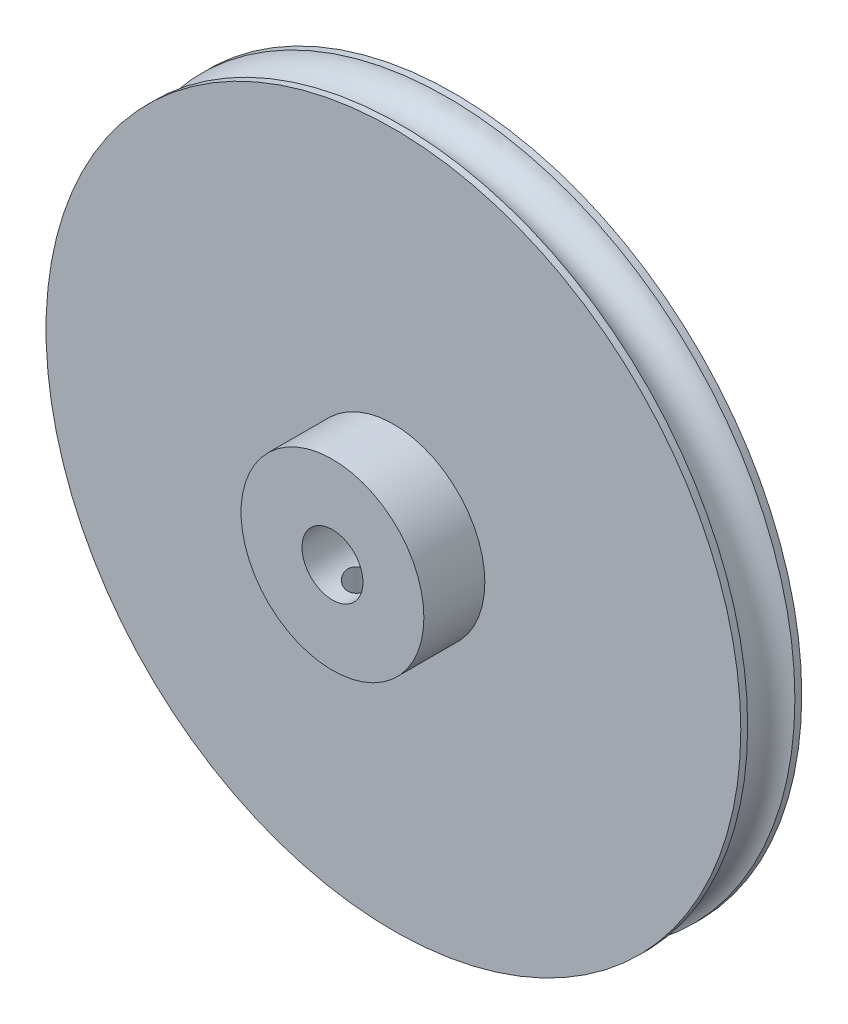
SolidWorks part; units mm, degrees
ref_plane "Plan de face" through (0, 0, 0) normal (0, 0, 1) x (1, 0, 0)
ref_plane "Plan de dessus" through (0, 0, 0) normal (0, 1, 0) x (1, 0, 0)
ref_plane "Plan de droite" through (0, 0, 0) normal (1, 0, 0) x (0, 0, -1)
sketch "Esquisse1" plane through (0, 0, 0) normal (0, 0, 1) x (1, 0, 0)
  circle A0 centre (0, 0) radius 28.5
  dimension "D1" = 57
extrude "Extrusion1" add sketch "Esquisse1" against normal blind 5
sketch "Esquisse2" plane through (0, 0, 0) normal (0, 0, 1) x (1, 0, 0)
  circle A0 centre (0, 0) radius 7.5
  dimension "D1" = 15
extrude "Extrusion2" add sketch "Esquisse2" along normal blind 5
sketch "Esquisse3" plane through (0, 0, 5) normal (0, 0, 1) x (1, 0, 0)
  circle A0 centre (0, 0) radius 2.5
  dimension "D1" = 5
extrude "Extrusion3" cut sketch "Esquisse3" against normal up to next
sketch "Esquisse6" plane through (0, 0, 0) normal (0, 1, 0) x (1, 0, 0)
  line L0 (-29, 2.5) -> (-27, 2.5) construction
  line L1 (-29, 4.5) -> (-31.4496, 4.5)
  line L2 (-29, 0.5) -> (-31.4496, 0.5)
  line L3 (-28.5, 0) -> (28.5, 0) construction
  line L4 (-29, 0) -> (-29, 0.5) construction
  line L5 (-29, 5) -> (-29, 4.5) construction
  line L6 (28.5, 5) -> (-28.5, 5) construction
  line L7 (-31.4496, 0.5) -> (-31.4496, 4.5)
  line L8 (-29, 0.5) -> (-29, 2.5) construction
  arc A0 (-29, 0.5) -> (-29, 4.5) centre (-29, 2.5) ccw
  dimension "D1" = 2
  dimension "D2" = 0.5
  dimension "D3" = 27
revolve "Enlèvement de matière-Révolution3" cut sketch "Esquisse6" angle 360 about axis through (0, 0, 5) along (0, 0, -1)
ref_plane "Plan1" through (0, 0, 0) normal (0, 1, 0) x (1, 0, 0)
sketch "Esquisse11" plane through (0, 0, 0) normal (0, 1, 0) x (1, 0, 0)
  line L0 (0, 0) -> (0, -5) construction
  line L1 (-7.5, -5) -> (7.5, -5) construction
  point P5 (0, -2.5)
hole_wizard "Trou taraudé M3x0.55" positions "Esquisse13" profile "Esquisse12" tap size "M3x0.5" standard "Ansi Metric"
sketch "Esquisse13" plane through (0, 0, 0) normal (0, 1, 0) x (1, 0, 0)
  line L0 (0, 0) -> (0, -5) construction
  point P8 (0, -2.5)
sketch "Esquisse12" plane through (0, 0, 2.5) normal (1, 0, 0) x (0, 0, 1)
  line L0 (0, 0) -> (0, 28.5)
  line L1 (0, 28.5) -> (1.25, 28.5)
  line L2 (1.25, 28.5) -> (1.25, 0)
  line L5 (1.25, 0) -> (0, 0)
  line L11 (0, -6.35) -> (0, 107.95) construction
  dimension "Diamètre du trou pour taraudage jusqu'au prochain" = 2.5
  dimension "Profondeur du trou pour taraudage jusqu'au prochain" = 28.5
cosmetic thread "Filetage de perçage1" parameters "D2"=3
